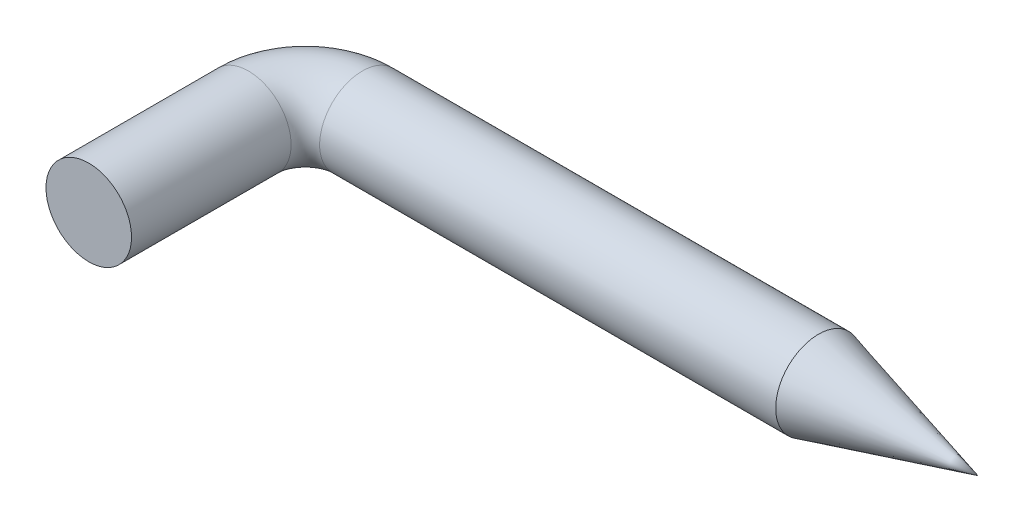
SolidWorks part; units mm, degrees
ref_plane "Plan de face" through (0, 0, 0) normal (0, 0, 1) x (1, 0, 0)
ref_plane "Plan de dessus" through (0, 0, 0) normal (0, 1, 0) x (1, 0, 0)
ref_plane "Plan de droite" through (0, 0, 0) normal (1, 0, 0) x (0, 0, -1)
sketch "Esquisse1" plane through (0, 0, 0) normal (0, 0, 1) x (1, 0, 0)
  circle A0 centre (0, 0) radius 7.5
  dimension "D1" = 15
sketch "Esquisse3" plane through (0, 0, 0) normal (0, 1, 0) x (1, 0, 0)
  line L0 (0, 0) -> (0, 28)
  line L1 (10, 38) -> (90, 38)
  arc A0 (0, 28) -> (10, 38) centre (10, 28) cw
  point P7 (0, 38)
  dimension "D3" = 10
  dimension "D1" = 38
  dimension "D2" = 90
sweep "Balayage1" add profiles "Esquisse1" path "Esquisse3"
sketch "Esquisse4" plane through (90, 0, 0) normal (1, 0, 0) x (0, 0, -1)
  circle A1 centre (38, 0) radius 7.5
  circle A2 centre (38, 0) radius 7.5
  dimension "D1" = 0
extrude "Boss.-Extru.2" add sketch "Esquisse4" along normal blind 44 draft 15
